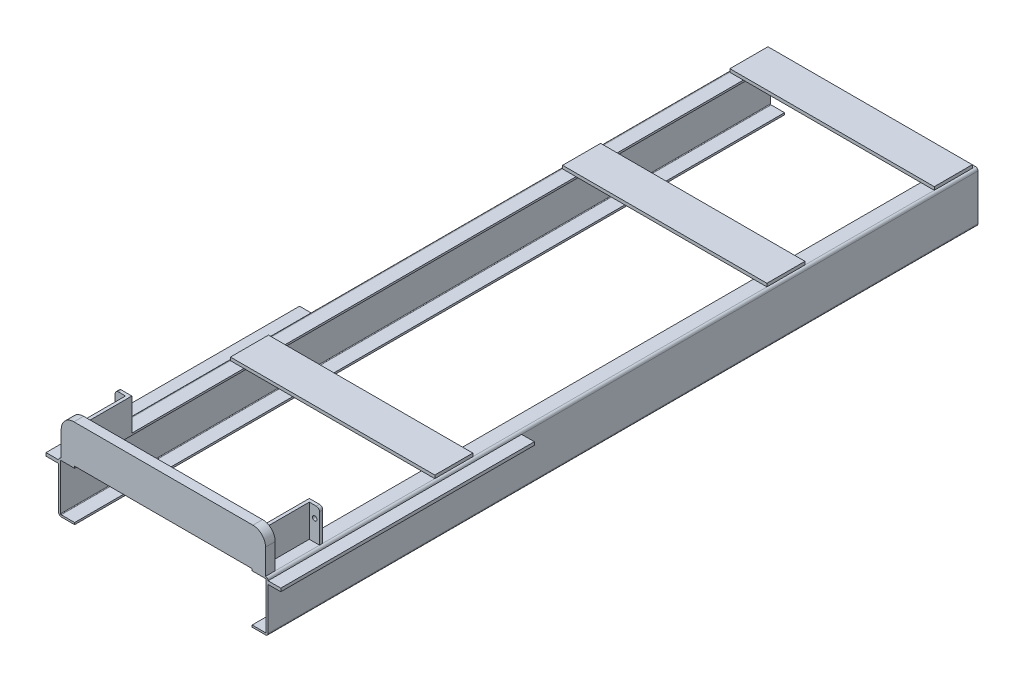
SolidWorks part; units mm, degrees
ref_plane "Front Plane" through (0, 0, 0) normal (0, 0, 1) x (1, 0, 0)
ref_plane "Top Plane" through (0, 0, 0) normal (0, 1, 0) x (1, 0, 0)
ref_plane "Right Plane" through (0, 0, 0) normal (1, 0, 0) x (0, 0, -1)
sketch "Sketch1" plane through (0, 0, 0) normal (0, 0, 1) x (1, 0, 0)
  line L0 (0, 0) -> (413, 0) construction
  line L1 (350, 100) -> (403, 100)
  line L2 (413, 90) -> (413, -90)
  line L3 (403, -100) -> (350, -100)
  arc A0 (413, -90) -> (403, -100) centre (403, -90) cw
  arc A1 (403, 100) -> (413, 90) centre (403, 90) cw
  point P9 (413, -100)
  point P12 (413, 100)
  dimension "D4" = 10
  dimension "D1" = 413
  dimension "D2" = 200
  dimension "D3" = 63
extrude "Extrude-Thin1" add sketch "Sketch1" along normal mid plane 2800 thin
sketch "Sketch2" plane through (0, 0, 1400) normal (0, 0, 1) x (1, 0, 0)
  line L0 (413, 90) -> (413, -90) construction
  line L1 (413, 90) -> (463, 90)
  line L2 (413, 90) -> (413, 77.5)
  line L3 (413, 77.5) -> (463, 77.5)
  line L4 (463, 90) -> (463, 77.5)
  arc A0 (413, 90) -> (403, 100) centre (403, 90) ccw construction
  dimension "D1" = 50
  dimension "D2" = 12.5
extrude "Boss-Extrude1" add sketch "Sketch2" against normal blind 1000
mirror "Mirror4" about plane through (0, 0, 0) normal (1, 0, 0) of bodies 102
sketch "Sketch4" plane through (0, 0, 1400) normal (0, 0, 1) x (1, 0, 0)
  line L1 (-403, 100) -> (403, 100)
  line L2 (-403, 100) -> (-403, 200)
  line L3 (-353, 250) -> (353, 250)
  line L4 (403, 100) -> (403, 200)
  arc A0 (-403, 200) -> (-353, 250) centre (-353, 200) cw
  arc A1 (353, 250) -> (403, 200) centre (353, 200) cw
  point P9 (403, 250)
  dimension "D2" = 50
  dimension "D1" = 150
extrude "Boss-Extrude2" add sketch "Sketch4" against normal blind 38
sketch "Sketch5" plane through (0, 100, 0) normal (0, 1, 0) x (1, 0, 0)
  line L0 (-403, -1362) -> (-403, 1400) construction
  line L1 (-403, 1387.5) -> (403, 1387.5)
  line L2 (-403, 1387.5) -> (-403, 1237.5)
  line L3 (-403, 1237.5) -> (403, 1237.5)
  line L4 (403, 1387.5) -> (403, 1237.5)
  line L5 (403, -1362) -> (403, 1400) construction
  line L6 (350, 1400) -> (403, 1400) construction
  dimension "D1" = 12.5
  dimension "D2" = 150
extrude "Boss-Extrude3" add sketch "Sketch5" along normal blind 12.5
pattern_linear "LPattern1" count 2 spacing 660 along (0, 0, 1) of "Boss-Extrude3"
pattern_linear "LPattern2" count 2 spacing 1970 along (0, 0, 1) of "Boss-Extrude3"
sketch "Sketch6" plane through (0, 0, 1362) normal (0, 0, -1) x (-1, 0, 0)
  line L1 (-350, 100) -> (-362.5, 100)
  line L2 (-350, 100) -> (-350, 227)
  line L3 (-350, 227) -> (-362.5, 227)
  line L4 (-362.5, 100) -> (-362.5, 227)
  dimension "D1" = 127
  dimension "D2" = 12.5
extrude "Boss-Extrude4" add sketch "Sketch6" along normal blind 175
sketch "Sketch7" plane through (0, 0, 1187) normal (0, 0, -1) x (-1, 0, 0)
  line L1 (-350, 100) -> (-403, 100)
  line L2 (-350, 100) -> (-350, 227)
  line L3 (-350, 227) -> (-403, 227)
  line L4 (-403, 100) -> (-403, 227)
  circle A0 centre (-384, 182) radius 8.75
  dimension "D1" = 17.5
  dimension "D2" = 82
  dimension "D3" = 19
extrude "Boss-Extrude5" add sketch "Sketch7" along normal blind 12.5
fillet "Fillet1" radius 12.5 1 edges at (403, 227, 1180.75)
mirror "Mirror5" about plane through (0, 0, 0) normal (1, 0, 0) of "Fillet1", "Boss-Extrude5", "Boss-Extrude4"
